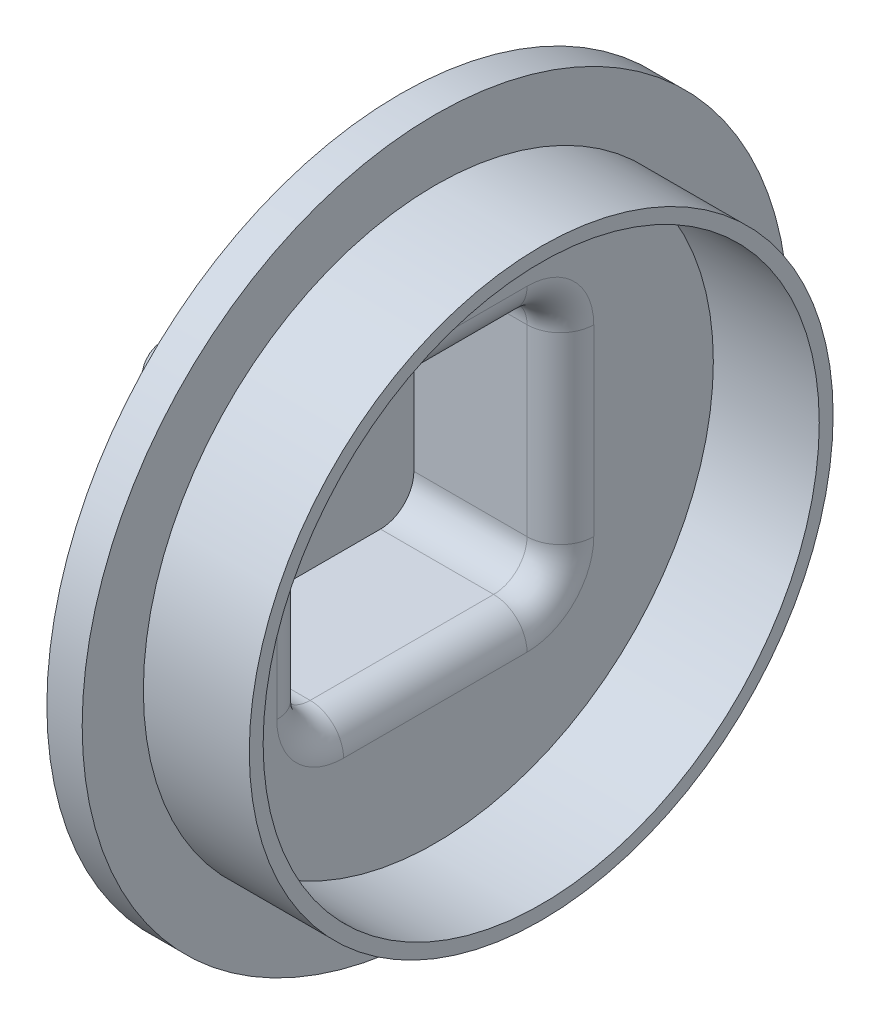
SolidWorks part; units mm, degrees
ref_plane "Front Plane" through (0, 0, 0) normal (0, 0, 1) x (1, 0, 0)
ref_plane "Top Plane" through (0, 0, 0) normal (0, 1, 0) x (1, 0, 0)
ref_plane "Right Plane" through (0, 0, 0) normal (1, 0, 0) x (0, 0, -1)
sketch "Sketch1" plane through (0, 0, 0) normal (1, 0, 0) x (0, 0, -1)
  circle A0 centre (0, 0) radius 63.5
  dimension "D1" = 127
extrude "Boss-Extrude1" add sketch "Sketch1" along normal blind 6.35
sketch "Sketch2" plane through (6.35, 0, 0) normal (1, 0, 0) x (0, 0, -1)
  circle A0 centre (0, 0) radius 52.5
  circle A1 centre (0, 0) radius 50.0063
  dimension "D1" = 105
  dimension "D2" = 100.0125
extrude "Boss-Extrude2" add sketch "Sketch2" along normal blind 19.05
sketch "Sketch3" plane through (0, 0, 0) normal (-1, 0, 0) x (0, 0, 1)
  line L1 (-25, 25) -> (25, 25)
  line L2 (-25, 25) -> (-25, -25)
  line L3 (-25, -25) -> (25, -25)
  line L4 (25, 25) -> (25, -25)
  line L5 (-25, 25) -> (25, -25) construction
  line L6 (-25, -25) -> (25, 25) construction
  point P0 (0, 0)
  dimension "D1" = 50
extrude "Boss-Extrude3" add sketch "Sketch3" along normal blind 25
sketch "Sketch4" plane through (6.35, 0, 0) normal (1, 0, 0) x (0, 0, -1)
  line L1 (-22.5, 22.5) -> (22.5, 22.5)
  line L2 (-22.5, 22.5) -> (-22.5, -22.5)
  line L3 (-22.5, -22.5) -> (22.5, -22.5)
  line L4 (22.5, 22.5) -> (22.5, -22.5)
  line L5 (-22.5, 22.5) -> (22.5, -22.5) construction
  line L6 (-22.5, -22.5) -> (22.5, 22.5) construction
  point P0 (0, 0)
  dimension "D1" = 45
extrude "Cut-Extrude1" cut sketch "Sketch4" against normal offset from surface (26.35 mm away) 5 up to face at (-25, 0, 0)
fillet "Fillet1" radius 6 16 edges at (-25, -25, 0) (-25, 0, -25) (-25, 25, 0) (-25, 0, 25) (-12.5, -25, -25) (-12.5, -25, 25) (-12.5, 25, 25) (-12.5, 25, -25) (6.35, -22.5, 0) (-6.825, -22.5, 22.5) (-6.825, -22.5, -22.5) (-6.825, 22.5, -22.5) (-6.825, 22.5, 22.5) (6.35, 0, 22.5) (6.35, 22.5, 0) (6.35, 0, -22.5)
